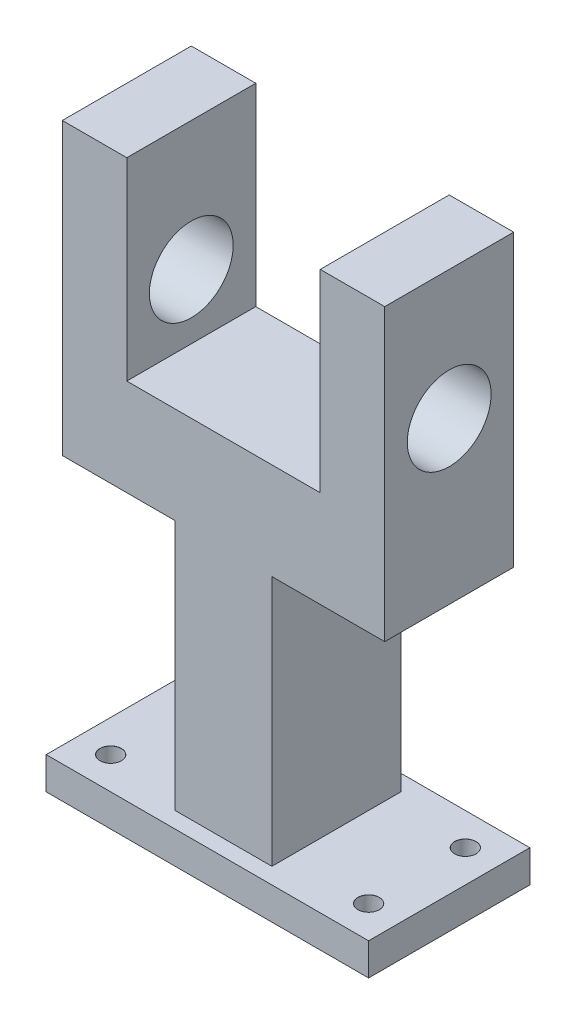
SolidWorks part; units mm, degrees
ref_plane "Front Plane" through (0, 0, 0) normal (0, 0, 1) x (1, 0, 0)
ref_plane "Top Plane" through (0, 0, 0) normal (0, 1, 0) x (1, 0, 0)
ref_plane "Right Plane" through (0, 0, 0) normal (1, 0, 0) x (0, 0, -1)
sketch "Sketch1" plane through (0, 0, 0) normal (0, 1, 0) x (1, 0, 0)
  line L1 (-50, 25) -> (50, 25)
  line L2 (-50, 25) -> (-50, -25)
  line L3 (-50, -25) -> (50, -25)
  line L4 (50, 25) -> (50, -25)
  line L5 (-50, 25) -> (50, -25) construction
  line L6 (-50, -25) -> (50, 25) construction
  point P0 (0, 0)
  dimension "D1" = 50
  dimension "D2" = 100
extrude "Boss-Extrude1" add sketch "Sketch1" along normal blind 10
hole_wizard "M6 Clearance Hole1" positions "Sketch2" profile "Sketch3" hole size "M6" standard "ANSI Metric" end condition up to next
sketch "Sketch2" plane through (0, 10, 0) normal (0, 1, 0) x (1, 0, 0)
  line L0 (-40, 15) -> (40, 15) construction
  line L2 (-40, 15) -> (-40, -15) construction
  line L4 (-50, 25) -> (-50, -25) construction
  line L5 (50, 25) -> (-50, 25) construction
  point P0 (-40, 15)
  point P2 (40, 15)
  point P4 (-40, -15)
  point P6 (40, -15)
  point P17 (-40, 0)
  point P19 (0, 15)
  dimension "D1" = 10
  dimension "D2" = 10
sketch "Sketch3" plane through (-40, 10, -15) normal (1, 0, 0) x (0, 0, 1)
  line L0 (0, 0) -> (0, 10)
  line L1 (0, 10) -> (3.3, 10)
  line L2 (3.3, 10) -> (3.3, 0.021)
  line L3 (3.3, 0.021) -> (3.325, 0)
  line L5 (3.325, 0) -> (0, 0)
  line L6 (-3.3, 0.021) -> (-3.325, 0) construction
  line L11 (0, -6.35) -> (0, 107.95) construction
  dimension "Thru Hole Dia." = 6.6
  dimension "Thru Hole Depth" = 10
  dimension "Near C'Sink Dia." = 6.65
  dimension "Near C'Sink Angle" = 100
sketch "Sketch4" plane through (0, 10, 0) normal (0, 1, 0) x (1, 0, 0)
  line L0 (50, 25) -> (-50, 25) construction
  line L1 (-15, -20) -> (15, -20)
  line L2 (-15, -20) -> (-15, 20)
  line L3 (-15, 20) -> (15, 20)
  line L4 (15, -20) -> (15, 20)
  line L5 (-15, -20) -> (15, 20) construction
  line L6 (-15, 20) -> (15, -20) construction
  point P0 (0, 0)
  point P12 (15, 0)
  dimension "D1" = 30
  dimension "D4" = 5
extrude "Boss-Extrude2" add sketch "Sketch4" along normal blind 107.84
sketch "Sketch6" plane through (0, 0, 0) normal (1, 0, 0) x (0, 0, -1)
  line L0 (20, 117.84) -> (20, 10) construction
  line L1 (-20, 117.84) -> (20, 117.84)
  line L2 (-20, 117.84) -> (-20, 87.84)
  line L3 (-20, 87.84) -> (20, 87.84)
  line L4 (20, 117.84) -> (20, 87.84)
  dimension "D1" = 30
extrude "Boss-Extrude3" add sketch "Sketch6" along normal blind 50 and the other way blind 50
sketch "Sketch7" plane through (0, 117.84, 0) normal (0, 1, 0) x (1, 0, 0)
  line L0 (-50, -20) -> (50, -20) construction
  line L1 (-50, 20) -> (-30, 20)
  line L2 (-50, 20) -> (-50, -20)
  line L3 (-50, -20) -> (-30, -20)
  line L4 (-30, 20) -> (-30, -20)
  line L6 (50, 20) -> (30, 20)
  line L7 (50, 20) -> (50, -20)
  line L8 (50, -20) -> (30, -20)
  line L9 (30, 20) -> (30, -20)
  dimension "D1" = 20
extrude "Boss-Extrude4" add sketch "Sketch7" along normal blind 60
sketch "Sketch8" plane through (-50, 0, 0) normal (-1, 0, 0) x (0, 0, 1)
  line L0 (20, 87.84) -> (-20, 87.84) construction
  circle A0 centre (0, 137.84) radius 13
  dimension "D1" = 26
  dimension "D2" = 50
extrude "Cut-Extrude3" cut sketch "Sketch8" against normal through all
